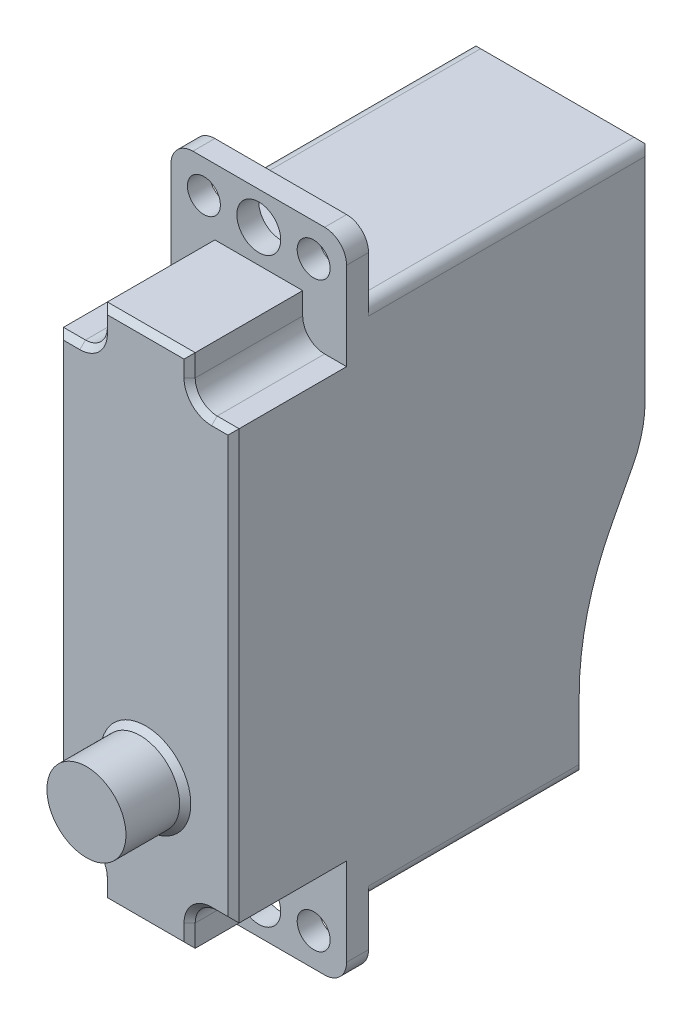
SolidWorks part; units mm, degrees
material "6061 Alloy"
ref_plane "Front Plane" through (0, 0, 0) normal (1, 0, 0) x (0, 1, 0)
ref_plane "Top Plane" through (0, 0, 0) normal (0, 0, 1) x (0, 1, 0)
ref_plane "Right Plane" through (0, 0, 0) normal (0, 1, 0) x (-1, 0, 0)
sketch "Sketch1" plane through (0, 0, 0) normal (1, 0, 0) x (0, 1, 0)
  line L0 (0, 0) -> (23.5, 0)
  line L1 (23.5, 0) -> (23.5, -5.15)
  line L2 (23.5, -5.15) -> (26.5, -5.15)
  line L3 (26.5, -5.15) -> (26.5, -6.15)
  line L4 (26.5, -6.15) -> (23.5, -6.15)
  line L5 (23.5, -6.15) -> (23.5, -19)
  line L6 (23.5, -19) -> (13.3213, -19)
  line L7 (10.9618, -18.4188) -> (9.1204, -17.453)
  line L8 (3.2217, -16) -> (0, -16)
  line L9 (0, -16) -> (0, -6.15)
  line L10 (0, -6.15) -> (-3, -6.15)
  line L11 (-3, -6.15) -> (-3, -5.15)
  line L12 (-3, -5.15) -> (0, -5.15)
  line L13 (0, -5.15) -> (0, 0)
  arc A0 (13.3213, -19) -> (10.9618, -18.4188) centre (13.3213, -13.92) cw
  arc A1 (9.1204, -17.453) -> (3.2217, -16) centre (3.2217, -28.7) ccw
  point P17 (12.07, -19)
  point P20 (6.35, -16)
  dimension "D9" = 5.08
  dimension "D10" = 12.7
  dimension "D1" = 19
  dimension "D2" = 5.15
  dimension "D3" = 23.5
  dimension "D4" = 29.5
  dimension "D5" = 1
  dimension "D6" = 3
  dimension "D7" = 11.43
  dimension "D8" = 6.35
extrude "Boss-Extrude1" add sketch "Sketch1" along normal blind 8
sketch "Sketch2" plane through (0, 0, -5.15) normal (0, 0, 1) x (1, 0, 0)
  line L0 (8, 26.5) -> (0, 26.5) construction
  line L1 (4, 25) -> (4, -1.5) construction
  line L2 (0, 23.5) -> (0, 0) construction
  line L3 (1.5, 25) -> (6.5, 25) construction
  circle A0 centre (4, -1.5) radius 1
  circle A1 centre (4, 25) radius 1
  circle A2 centre (6.5, 25) radius 0.75
  circle A3 centre (1.5, 25) radius 0.75
  circle A4 centre (1.5, -1.5) radius 0.75
  circle A5 centre (6.5, -1.5) radius 0.75
  point P6 (4, 26.5)
  point P7 (4, 11.75)
  point P10 (0, 11.75)
  point P19 (4, 25)
  point P20 (0, 0)
  point P21 (0, 0)
  point P22 (1.5, -1.5)
  dimension "D1" = 2
  dimension "D2" = 2
  dimension "D4" = 1.5
  dimension "D3" = 26.5
  dimension "D5" = 5
extrude "Cut-Extrude1" cut sketch "Sketch2" against normal through all
fillet "Fillet1" radius 1 4 edges at (0, -3, -5.65) (8, -3, -5.65) (0, 26.5, -5.65) (8, 26.5, -5.65)
sketch "Sketch3" plane through (0, 0, 0) normal (0, 0, 1) x (1, 0, 0)
  line L0 (8, 0) -> (0, 0) construction
  circle A0 centre (4, 5.85) radius 1.8
  point P4 (0, 0)
  point P5 (4, 0)
  dimension "D2" = 3.6
  dimension "D1" = 5.85
extrude "Boss-Extrude2" add sketch "Sketch3" along normal blind 2.7
sketch "Sketch4" plane through (0, 0, 0) normal (0, 0, 1) x (1, 0, 0)
  line L1 (0, 23.5) -> (2, 23.5)
  line L2 (0, 23.5) -> (0, 21.5)
  line L3 (0, 21.5) -> (1, 21.5)
  line L4 (2, 23.5) -> (2, 22.5)
  line L5 (8, 23.5) -> (6, 23.5)
  line L6 (8, 23.5) -> (8, 21.5)
  line L7 (8, 21.5) -> (7, 21.5)
  line L8 (6, 23.5) -> (6, 22.5)
  line L9 (0, 0) -> (2, 0)
  line L10 (0, 0) -> (0, 2)
  line L11 (0, 2) -> (1, 2)
  line L12 (2, 0) -> (2, 1)
  line L13 (8, 0) -> (6, 0)
  line L14 (8, 0) -> (8, 2)
  line L15 (8, 2) -> (7, 2)
  line L16 (6, 0) -> (6, 1)
  arc A0 (1, 2) -> (2, 1) centre (1, 1) cw
  arc A1 (7, 2) -> (6, 1) centre (7, 1) ccw
  arc A2 (7, 21.5) -> (6, 22.5) centre (7, 22.5) cw
  arc A3 (1, 21.5) -> (2, 22.5) centre (1, 22.5) ccw
  point P20 (2, 1.9483)
  dimension "D2" = 1
  dimension "D1" = 2
extrude "Cut-Extrude2" cut sketch "Sketch4" against normal up to surface (5.15 mm away) up to face at (5, 25, -5.15)
chamfer "Chamfer1" distance 0.254 angle 45 17 edges at (7.5, 21.5, 0) (8, 11.75, 0) (7.5, 2, 0) (6.2929, 1.7071, 0) (6, 0.5, 0) (4, 0, 0) (2, 0.5, 0) (1.7071, 1.7071, 0) (0.5, 2, 0) (0, 11.75, 0) (0.5, 21.5, 0) (1.7071, 21.7929, 0) (2, 23, 0) (4, 23.5, 0) (6, 23, 0) (6.2929, 21.7929, 0) (2.2, 5.85, 0)
chamfer "Chamfer2" distance 0.254 angle 45 12 edges at (4, 0, -16) (0, 1.6108, -16) (8, 1.6108, -16) (0, 6.2592, -16.3686) (8, 6.2592, -16.3686) (0, 10.0411, -17.9359) (8, 10.0411, -17.9359) (0, 12.1063, -18.8526) (8, 12.1063, -18.8526) (0, 18.4107, -19) (4, 23.5, -19) (8, 18.4107, -19)
fillet "Fillet2" radius 0.508 4 edges at (0, 0, -10.948) (8, 0, -10.948) (0, 23.5, -12.448) (8, 23.5, -12.448)
